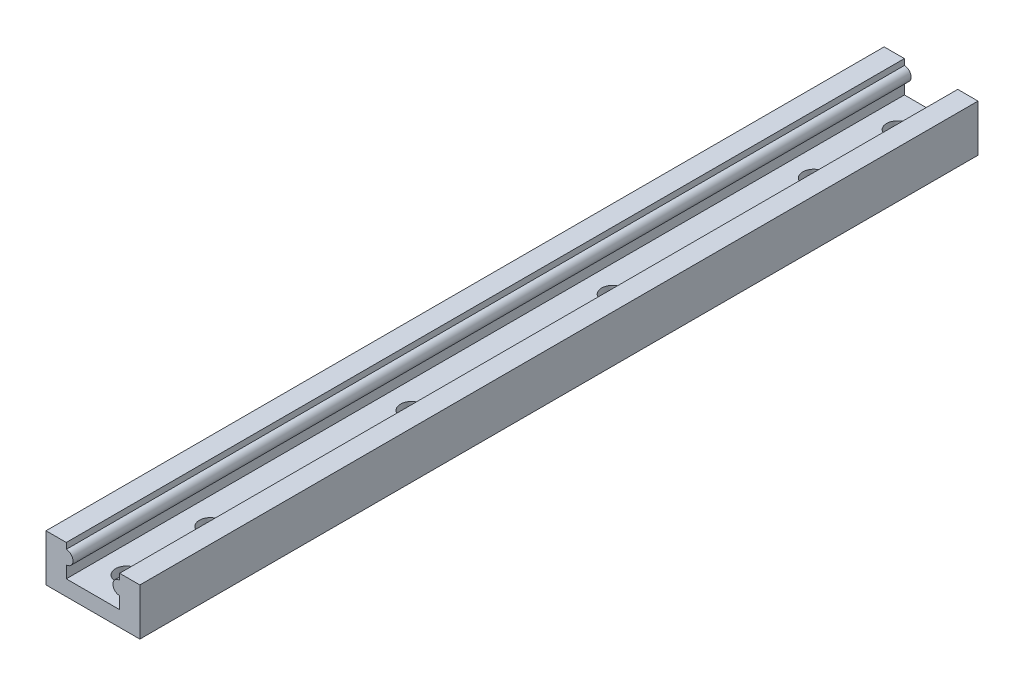
SolidWorks part; units mm, degrees
material "自定义塑料"
ref_plane "前视基准面" through (0, 0, 0) normal (0, 0, 1) x (1, 0, 0)
ref_plane "上视基准面" through (0, 0, 0) normal (0, 1, 0) x (1, 0, 0)
ref_plane "右视基准面" through (0, 0, 0) normal (1, 0, 0) x (0, 0, -1)
sketch "草图1" plane through (0, 0, 0) normal (0, 0, 1) x (1, 0, 0)
  line L0 (7.9552, 8.1538) -> (7.9552, -5.1818) construction
  line L1 (-6.0448, 8.1674) -> (0, 8.1674)
  line L2 (-6.0448, 8.1674) -> (-6.0448, -5.8326)
  line L3 (-6.0448, -5.8326) -> (21.9552, -5.8326)
  line L4 (21.9552, 8.1674) -> (21.9552, -5.8326)
  line L5 (0, 8.1674) -> (0, 6.3763)
  line L6 (0, -1.2326) -> (15.9105, -1.2326)
  line L7 (15.9105, 8.1674) -> (15.9105, 6.3763)
  line L8 (15.9105, 8.1674) -> (21.9552, 8.1674)
  line L9 (0, 2.3763) -> (0, -1.2326)
  line L10 (15.9105, 2.3763) -> (15.9105, -1.2326)
  arc A0 (0, 2.3763) -> (0, 6.3763) centre (0, 4.3763) ccw
  arc A1 (15.9105, 2.3763) -> (15.9105, 6.3763) centre (15.9105, 4.3763) cw
  point P11 (7.9552, -1.2326)
  dimension "D4" = 4
  dimension "D1" = 28
  dimension "D2" = 14
  dimension "D3" = 4.6
extrude "凸台-拉伸1" add sketch "草图1" along normal blind 250
sketch "草图2" plane through (0, -5.8326, 0) normal (0, -1, 0) x (1, 0, 0)
  line L0 (7.9552, 250) -> (7.9552, -49750) construction
  line L1 (-6.0448, 250) -> (21.9552, 250) construction
  line L2 (-6.0448, 0) -> (21.9552, 0) construction
  line L3 (15.9105, 0) -> (0, 0) construction
  line L4 (15.9105, 250) -> (0, 250) construction
  circle A0 centre (7.9552, 215) radius 1.75
  circle A1 centre (7.9552, 155) radius 1.75
  circle A2 centre (7.9552, 95) radius 1.75
  circle A3 centre (7.9552, 35) radius 1.75
  circle A4 centre (7.9552, -25) radius 1.75
  circle A5 centre (7.9552, -85) radius 1.75
  circle A6 centre (7.9552, 10) radius 1.6
  circle A7 centre (7.9552, 240) radius 1.6
  point P4 (7.9552, 250)
  point P7 (7.9552, 0)
  dimension "D1" = 3.5
  dimension "D4" = 3.2
  dimension "D6" = 3.2
  dimension "D2" = 35
  dimension "D5" = 10
  dimension "D7" = 10
  dimension "D3" = 6
extrude "切除-拉伸1" cut sketch "草图2" against normal through all
sketch "草图3" plane through (0, -1.2326, 0) normal (0, 1, 0) x (1, 0, 0)
  line L0 (7.9552, 0) -> (7.9552, -50000) construction
  line L1 (15.9105, 0) -> (0, 0) construction
  circle A0 centre (7.9552, -35) radius 3.25
  circle A1 centre (7.9552, -95) radius 3.25
  circle A2 centre (7.9552, -155) radius 3.25
  circle A3 centre (7.9552, -215) radius 3.25
  circle A4 centre (7.9552, -275) radius 3.25
  circle A5 centre (7.9552, -240) radius 3.25
  circle A6 centre (7.9552, -10) radius 3.25
  point P40 (7.9552, 0)
  dimension "D1" = 6.5
  dimension "D3" = 6.5
  dimension "D4" = 6.5
  dimension "D2" = 5
extrude "切除-拉伸2" cut sketch "草图3" against normal blind 3
